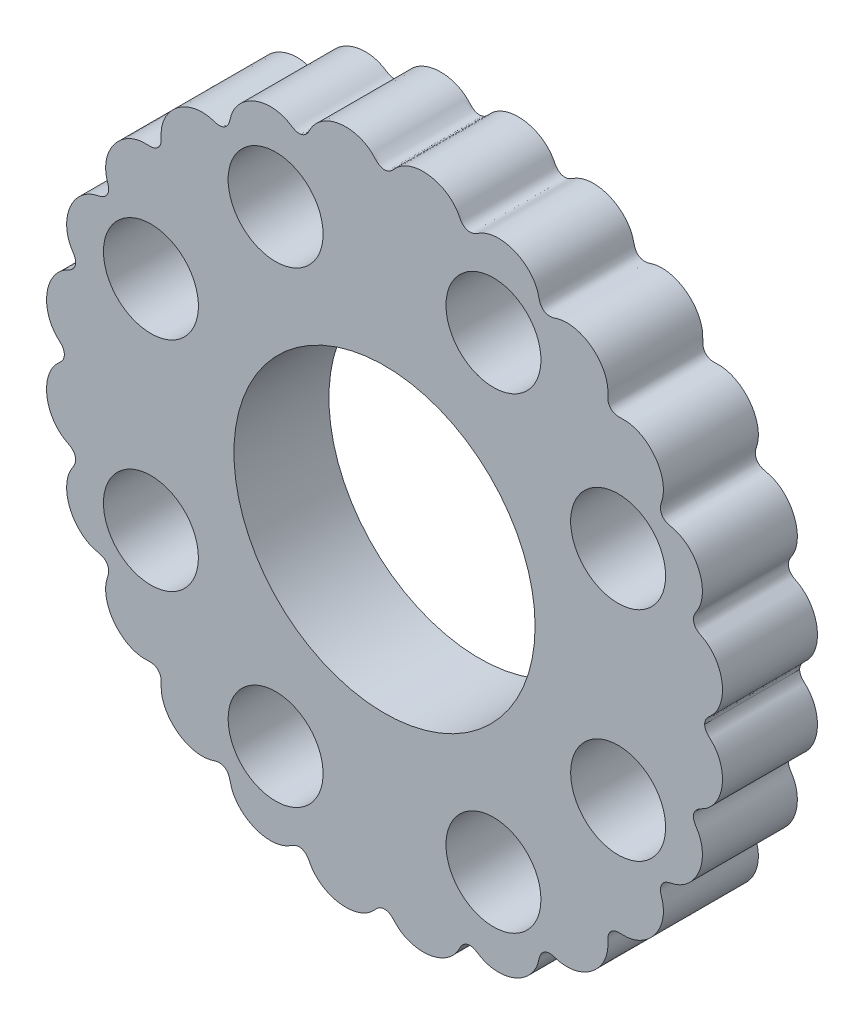
SolidWorks part; units mm, degrees
ref_plane "Plan de face" through (0, 0, 0) normal (0, 0, 1) x (1, 0, 0)
ref_plane "Plan de dessus" through (0, 0, 0) normal (0, 1, 0) x (1, 0, 0)
ref_plane "Plan de droite" through (0, 0, 0) normal (1, 0, 0) x (0, 0, -1)
sketch "Esquisse1" plane through (0, 0, 0) normal (0, 0, 1) x (1, 0, 0)
  line L0 (-1000, 0) -> (49000, 0) construction
  spline S0 degree 4 poles (22.9955, 6.6042) (22.9643, 6.5397) (22.914, 6.4032) (22.9023, 6.1862) (23.0214, 5.9244) (23.2219, 5.7605) (23.4288, 5.659) (23.6594, 5.5306) (23.9059, 5.3649) (24.1666, 5.1353) (24.4254, 4.835) (24.6422, 4.5029) (24.8162, 4.1468) (24.946, 3.7722) (25.0308, 3.385) (25.0698, 2.9906) (25.0624, 2.5943) (25.0079, 2.2017) (24.9068, 1.8224) (24.7781, 1.5066) (24.64, 1.2523) (24.5081, 1.0548) (24.3917, 0.9046) (24.2647, 0.7631) (24.1289, 0.6302) (24.012, 0.5251) (23.9248, 0.4355) (23.8688, 0.3622) (23.8363, 0.3122) (23.8082, 0.2597) (23.7852, 0.2044) (23.7697, 0.1547) (23.76, 0.1121) (23.7533, 0.0661) (23.7501, 0.0228) (23.7495, -0.004) (23.7513, -0.04) (23.7542, -0.0715) (23.7595, -0.1093) (23.7688, -0.1512) (23.7835, -0.1997) (23.8056, -0.2538) (23.8324, -0.3054) (23.8635, -0.3546) (23.9194, -0.4297) (24.009, -0.5227) (24.1313, -0.6322) (24.2737, -0.7721) (24.4392, -0.959) (24.6145, -1.2025) (24.7855, -1.5135) (24.9316, -1.8961) (25.0271, -2.299) (25.0708, -2.7153) (25.0622, -3.1311) (25.0033, -3.5401) (24.8958, -3.9363) (24.7419, -4.314) (24.5445, -4.6645) (24.307, -4.9822) (24.0331, -5.2614) (23.7654, -5.4667) (23.5164, -5.6129) (23.2956, -5.7243) (23.1195, -5.8363) (22.9763, -6.0087) (22.9044, -6.234) (22.925, -6.462) (23.0164, -6.6581) (23.1266, -6.8267) (23.2244, -6.9889) (23.3341, -7.1984) (23.4412, -7.4619) (23.5336, -7.7957) (23.5876, -8.2004) (23.5865, -8.623) (23.5267, -9.0558) (23.3808, -9.5868) (23.1436, -10.0885) (22.8209, -10.5434) (22.4327, -10.9196) (22.1006, -11.1627) (21.7948, -11.3267) (21.5321, -11.4304) (21.3065, -11.4954) (21.1232, -11.5381) (20.9306, -11.5808) (20.7385, -11.6689) (20.5325, -11.8672) (20.4495, -12.16) (20.5219, -12.4298) (20.6167, -12.7241) (20.6818, -13.0067) (20.7176, -13.3406) (20.7046, -13.7295) (20.6405, -14.1156) (20.5273, -14.4945) (20.3673, -14.8595) (20.1602, -15.2112) (19.9061, -15.5428) (19.6059, -15.8469) (19.261, -16.115) (18.8955, -16.3273) (18.5181, -16.4829) (18.1828, -16.5697) (17.9011, -16.6087) (17.6647, -16.6185) (17.4754, -16.6149) (17.2743, -16.6037) (17.0588, -16.6226) (16.851, -16.7187) (16.6918, -16.8937) (16.6141, -17.104) (16.6052, -17.3124) (16.6191, -17.5593) (16.617, -17.8481) (16.5731, -18.1826) (16.4683, -18.5594) (16.3118, -18.9239) (16.107, -19.2701) (15.8569, -19.5923) (15.5674, -19.8834) (15.2427, -20.1389) (14.8869, -20.3543) (14.5046, -20.5246) (14.1078, -20.6433) (13.7035, -20.7081) (13.2985, -20.7166) (12.9508, -20.673) (12.6603, -20.5981) (12.4161, -20.517) (12.2029, -20.4723) (11.9744, -20.5019) (11.768, -20.6211) (11.6281, -20.8042) (11.5602, -21.0112) (11.5084, -21.2632) (11.428, -21.5523) (11.2919, -21.8752) (11.082, -22.2216) (10.8237, -22.5394) (10.5226, -22.8236) (10.1839, -23.0696) (9.8195, -23.2701) (9.4358, -23.4235) (9.039, -23.5286) (8.6349, -23.5841) (8.2327, -23.5884) (7.8388, -23.5416) (7.4601, -23.444) (7.1484, -23.3148) (6.8973, -23.1723) (6.6904, -23.0367) (6.5054, -22.9402) (6.2844, -22.9024) (6.0534, -22.9528) (5.8662, -23.0846) (5.7421, -23.2618) (5.6512, -23.4416) (5.5596, -23.6073) (5.4331, -23.8072) (5.2584, -24.0316) (5.0155, -24.2786) (4.6921, -24.5276) (4.2308, -24.7924) (3.7121, -24.9769) (3.1672, -25.0695) (2.6142, -25.0665) (2.1723, -25.0046) (1.7597, -24.8871) (1.3831, -24.721) (1.0882, -24.5382) (0.867, -24.3625) (0.6979, -24.1997) (0.5693, -24.0623) (0.436, -23.9168) (0.2637, -23.7945) (-0.011, -23.7153) (-0.3061, -23.7898) (-0.5036, -23.9874) (-0.7111, -24.2166) (-0.9232, -24.4143) (-1.1945, -24.6122) (-1.5378, -24.7955) (-1.9042, -24.933) (-2.289, -25.0244) (-2.6851, -25.0684) (-3.0932, -25.0648) (-3.5074, -25.0106) (-3.9209, -24.9026) (-4.3256, -24.738) (-4.6921, -24.5276) (-5.0155, -24.2786) (-5.2584, -24.0316) (-5.4331, -23.8072) (-5.5596, -23.6073) (-5.6512, -23.4416) (-5.7421, -23.2618) (-5.8662, -23.0846) (-6.0534, -22.9528) (-6.2844, -22.9024) (-6.5054, -22.9402) (-6.6904, -23.0367) (-6.8973, -23.1723) (-7.1484, -23.3148) (-7.4601, -23.444) (-7.8388, -23.5416) (-8.2327, -23.5884) (-8.6349, -23.5841) (-9.039, -23.5286) (-9.4358, -23.4235) (-9.8195, -23.2701) (-10.1839, -23.0696) (-10.5226, -22.8236) (-10.8237, -22.5394) (-11.082, -22.2216) (-11.2919, -21.8752) (-11.428, -21.5523) (-11.5084, -21.2632) (-11.5602, -21.0112) (-11.6281, -20.8042) (-11.768, -20.6211) (-11.9744, -20.5019) (-12.2029, -20.4723) (-12.4161, -20.517) (-12.6603, -20.5981) (-12.9508, -20.673) (-13.2985, -20.7166) (-13.7035, -20.7081) (-14.1078, -20.6433) (-14.6048, -20.4946) (-15.1642, -20.2163) (-15.6552, -19.8308) (-16.055, -19.3579) (-16.3118, -18.9239) (-16.4683, -18.5594) (-16.5731, -18.1826) (-16.617, -17.8481) (-16.6191, -17.5593) (-16.6052, -17.3124) (-16.6141, -17.104) (-16.6918, -16.8937) (-16.851, -16.7187) (-17.0588, -16.6226) (-17.2743, -16.6037) (-17.4754, -16.6149) (-17.6647, -16.6185) (-17.9011, -16.6087) (-18.1828, -16.5697) (-18.5181, -16.4829) (-18.8955, -16.3273) (-19.261, -16.1151) (-19.6059, -15.8469) (-19.9061, -15.5428) (-20.1602, -15.2112) (-20.3673, -14.8595) (-20.5273, -14.4945) (-20.6405, -14.1156) (-20.7046, -13.7294) (-20.7175, -13.3407) (-20.6818, -13.0066) (-20.6166, -12.7243) (-20.522, -12.4295) (-20.4494, -12.1605) (-20.5243, -11.8962) (-20.683, -11.7227) (-20.8176, -11.632) (-20.958, -11.5755) (-21.1234, -11.5373) (-21.3064, -11.4958) (-21.5321, -11.4302) (-21.7948, -11.3268) (-22.1006, -11.1626) (-22.4327, -10.9196) (-22.7408, -10.6211) (-23.0153, -10.2693) (-23.2393, -9.8862) (-23.4104, -9.4792) (-23.5267, -9.0558) (-23.5865, -8.623) (-23.5876, -8.2004) (-23.5336, -7.7957) (-23.4412, -7.4619) (-23.3341, -7.1984) (-23.2244, -6.9889) (-23.1266, -6.8267) (-23.0164, -6.6581) (-22.925, -6.462) (-22.9044, -6.234) (-22.9763, -6.0087) (-23.1195, -5.8363) (-23.2956, -5.7243) (-23.5164, -5.6129) (-23.7654, -5.4667) (-24.0331, -5.2614) (-24.307, -4.9822) (-24.5445, -4.6645) (-24.7419, -4.314) (-24.8958, -3.9363) (-25.0033, -3.5401) (-25.0622, -3.1311) (-25.0708, -2.7153) (-25.0271, -2.299) (-24.9316, -1.8961) (-24.7855, -1.5135) (-24.6145, -1.2025) (-24.4393, -0.959) (-24.2737, -0.7721) (-24.1313, -0.6321) (-23.9982, -0.5131) (-23.8995, -0.4084) (-23.8391, -0.3182) (-23.8055, -0.2539) (-23.7835, -0.1997) (-23.7688, -0.1512) (-23.7595, -0.1093) (-23.7542, -0.0715) (-23.7513, -0.04) (-23.7495, -0.0037) (-23.7502, 0.0234) (-23.7534, 0.0677) (-23.7604, 0.1144) (-23.7705, 0.1578) (-23.7867, 0.2087) (-23.8107, 0.2649) (-23.8399, 0.3183) (-23.8736, 0.369) (-23.9317, 0.4432) (-24.0215, 0.5339) (-24.141, 0.6413) (-24.279, 0.7779) (-24.4075, 0.9235) (-24.5249, 1.0783) (-24.6575, 1.2816) (-24.7976, 1.5478) (-24.9275, 1.8824) (-25.0256, 2.2876) (-25.071, 2.7111) (-25.0623, 3.1368) (-25.0002, 3.5582) (-24.8859, 3.9683) (-24.7199, 4.3608) (-24.4999, 4.7349) (-24.2231, 5.0813) (-23.9331, 5.3469) (-23.6469, 5.5411) (-23.3456, 5.7009) (-23.0735, 5.8417) (-22.8982, 6.1368) (-22.9147, 6.4027) (-22.9638, 6.54) (-22.9956, 6.6042) knots 0 0 0 0 0 0.002762 0.005524 0.008057 0.010589 0.012487 0.014385 0.018181 0.021977 0.025773 0.029569 0.033366 0.037162 0.040959 0.044755 0.048552 0.052348 0.056144 0.059791 0.061614 0.063437 0.06526 0.067083 0.068906 0.070729 0.071301 0.071873 0.072445 0.073016 0.073588 0.07416 0.074446 0.074731 0.075303 0.075582 0.075861 0.07614 0.076419 0.076977 0.077535 0.078093 0.078652 0.07921 0.079768 0.081683 0.083599 0.085515 0.08743 0.091261 0.095093 0.099101 0.103109 0.107118 0.111126 0.115032 0.118938 0.122843 0.126749 0.130438 0.134127 0.137815 0.13966 0.141504 0.143638 0.145771 0.148068 0.150364 0.15218 0.153996 0.155812 0.157628 0.16126 0.164892 0.169075 0.173257 0.177439 0.181621 0.190162 0.194433 0.198704 0.20231 0.205917 0.20772 0.209523 0.211327 0.21313 0.215313 0.217496 0.222107 0.223949 0.225791 0.229476 0.23316 0.236844 0.240662 0.24448 0.248298 0.252116 0.256299 0.260481 0.264663 0.268845 0.272477 0.276109 0.277925 0.279741 0.281557 0.283373 0.28567 0.287966 0.2901 0.292233 0.294078 0.295922 0.299611 0.3033 0.306988 0.310894 0.3148 0.318706 0.322612 0.32662 0.330628 0.334637 0.338645 0.342476 0.346307 0.350139 0.352054 0.35397 0.356202 0.358434 0.360667 0.362899 0.364815 0.36673 0.370561 0.374393 0.378224 0.382232 0.386241 0.390249 0.394257 0.398163 0.402069 0.405975 0.40988 0.413569 0.417258 0.420947 0.422791 0.424635 0.426769 0.428902 0.431199 0.433495 0.435311 0.437127 0.438943 0.440759 0.444392 0.448024 0.452206 0.456388 0.464752 0.469023 0.473294 0.477564 0.481835 0.485441 0.489048 0.490851 0.492655 0.494458 0.496261 0.498444 0.500627 0.505239 0.507081 0.508923 0.512607 0.516291 0.519975 0.523793 0.527611 0.53143 0.535248 0.53943 0.543612 0.547794 0.551976 0.555609 0.559241 0.561057 0.562873 0.564689 0.566505 0.568801 0.571098 0.573231 0.575365 0.577209 0.579053 0.582742 0.586431 0.59012 0.594025 0.597931 0.601837 0.605743 0.609751 0.61376 0.617768 0.621776 0.625607 0.629439 0.63327 0.635186 0.637101 0.639333 0.641566 0.643798 0.64603 0.647946 0.649861 0.653693 0.657524 0.661355 0.665364 0.669372 0.677388 0.6852 0.689106 0.693012 0.6967 0.700389 0.704078 0.705922 0.707767 0.7099 0.712034 0.71433 0.716627 0.718443 0.720259 0.722075 0.723891 0.727523 0.731155 0.735337 0.739519 0.743701 0.747884 0.751702 0.75552 0.759338 0.763156 0.76684 0.770525 0.774209 0.776051 0.777893 0.782504 0.784687 0.785779 0.78687 0.788673 0.790477 0.79228 0.794083 0.79769 0.801296 0.805567 0.809838 0.814108 0.818379 0.822561 0.826743 0.830926 0.835108 0.83874 0.842372 0.844188 0.846004 0.84782 0.849636 0.851932 0.854229 0.856362 0.858496 0.86034 0.862185 0.865873 0.869562 0.873251 0.877157 0.881063 0.884968 0.888874 0.892882 0.896891 0.900899 0.904907 0.908739 0.91257 0.914486 0.916401 0.918317 0.920232 0.921349 0.921907 0.922465 0.923023 0.923581 0.92386 0.924139 0.924418 0.924697 0.925281 0.925573 0.925865 0.926449 0.927033 0.927617 0.928201 0.928785 0.929369 0.931232 0.933095 0.934957 0.93682 0.938683 0.940546 0.944272 0.94835 0.952428 0.956506 0.960584 0.964661 0.968739 0.972817 0.976894 0.98129 0.985685 0.987883 0.99008 0.994476 0.997238 1 1 1 1 1 construction
  spline S1 degree 4 poles (23.75, 0) (23.75, -0.0062) (23.7502, -0.0186) (23.7513, -0.04) (23.7542, -0.0715) (23.7595, -0.1093) (23.7688, -0.1512) (23.7835, -0.1997) (23.8056, -0.2538) (23.8324, -0.3054) (23.8635, -0.3546) (23.9194, -0.4297) (24.009, -0.5227) (24.1313, -0.6322) (24.2737, -0.7721) (24.4392, -0.959) (24.6145, -1.2025) (24.7855, -1.5135) (24.9316, -1.8961) (25.0271, -2.299) (25.0708, -2.7153) (25.0622, -3.1311) (25.0033, -3.5401) (24.8958, -3.9363) (24.7419, -4.314) (24.5445, -4.6645) (24.307, -4.9822) (24.0331, -5.2614) (23.7654, -5.4667) (23.5164, -5.6129) (23.2956, -5.7243) (23.1195, -5.8363) (22.9763, -6.0087) (22.9044, -6.234) (22.925, -6.462) (23.0164, -6.6581) (23.1266, -6.8267) (23.2244, -6.9889) (23.3341, -7.1984) (23.4412, -7.4619) (23.5336, -7.7957) (23.5876, -8.2004) (23.5865, -8.623) (23.5267, -9.0558) (23.3808, -9.5868) (23.1436, -10.0885) (22.8209, -10.5434) (22.4327, -10.9196) (22.1006, -11.1627) (21.7948, -11.3267) (21.5321, -11.4304) (21.3065, -11.4954) (21.1232, -11.5381) (20.9306, -11.5808) (20.7385, -11.6689) (20.5325, -11.8672) (20.4495, -12.16) (20.5219, -12.4298) (20.6167, -12.7241) (20.6818, -13.0067) (20.7176, -13.3406) (20.7046, -13.7295) (20.6405, -14.1156) (20.5273, -14.4945) (20.3673, -14.8595) (20.1602, -15.2112) (19.9061, -15.5428) (19.6059, -15.8469) (19.261, -16.115) (18.8955, -16.3273) (18.5181, -16.4829) (18.1828, -16.5697) (17.9011, -16.6087) (17.6647, -16.6185) (17.4754, -16.6149) (17.2743, -16.6037) (17.0588, -16.6226) (16.851, -16.7187) (16.6918, -16.8937) (16.6141, -17.104) (16.6052, -17.3124) (16.6191, -17.5593) (16.617, -17.8481) (16.5731, -18.1826) (16.4683, -18.5594) (16.3118, -18.9239) (16.107, -19.2701) (15.8569, -19.5923) (15.5674, -19.8834) (15.2427, -20.1389) (14.8869, -20.3543) (14.5046, -20.5246) (14.1078, -20.6433) (13.7035, -20.7081) (13.2985, -20.7166) (12.9508, -20.673) (12.6603, -20.5981) (12.4161, -20.517) (12.2029, -20.4723) (11.9744, -20.5019) (11.768, -20.6211) (11.6281, -20.8042) (11.5602, -21.0112) (11.5084, -21.2632) (11.428, -21.5523) (11.2919, -21.8752) (11.082, -22.2216) (10.8237, -22.5394) (10.5226, -22.8236) (10.1839, -23.0696) (9.8195, -23.2701) (9.4358, -23.4235) (9.039, -23.5286) (8.6349, -23.5841) (8.2327, -23.5884) (7.8388, -23.5416) (7.4601, -23.444) (7.1484, -23.3148) (6.8973, -23.1723) (6.6904, -23.0367) (6.5054, -22.9402) (6.2844, -22.9024) (6.0534, -22.9528) (5.8662, -23.0846) (5.7421, -23.2618) (5.6512, -23.4416) (5.5596, -23.6073) (5.4331, -23.8072) (5.2584, -24.0316) (5.0155, -24.2786) (4.6921, -24.5276) (4.2308, -24.7924) (3.7121, -24.9769) (3.1672, -25.0695) (2.6142, -25.0665) (2.1723, -25.0046) (1.7597, -24.8871) (1.3831, -24.721) (1.0882, -24.5382) (0.867, -24.3625) (0.6979, -24.1997) (0.5693, -24.0623) (0.436, -23.9168) (0.2637, -23.7945) (-0.011, -23.7153) (-0.3061, -23.7898) (-0.5036, -23.9874) (-0.7111, -24.2166) (-0.9232, -24.4143) (-1.1945, -24.6122) (-1.5378, -24.7955) (-1.9042, -24.933) (-2.289, -25.0244) (-2.6851, -25.0684) (-3.0932, -25.0648) (-3.5074, -25.0106) (-3.9209, -24.9026) (-4.3256, -24.738) (-4.6921, -24.5276) (-5.0155, -24.2786) (-5.2584, -24.0316) (-5.4331, -23.8072) (-5.5596, -23.6073) (-5.6512, -23.4416) (-5.7421, -23.2618) (-5.8662, -23.0846) (-6.0534, -22.9528) (-6.2844, -22.9024) (-6.5054, -22.9402) (-6.6904, -23.0367) (-6.8973, -23.1723) (-7.1484, -23.3148) (-7.4601, -23.444) (-7.8388, -23.5416) (-8.2327, -23.5884) (-8.6349, -23.5841) (-9.039, -23.5286) (-9.4358, -23.4235) (-9.8195, -23.2701) (-10.1839, -23.0696) (-10.5226, -22.8236) (-10.8237, -22.5394) (-11.082, -22.2216) (-11.2919, -21.8752) (-11.428, -21.5523) (-11.5084, -21.2632) (-11.5602, -21.0112) (-11.6281, -20.8042) (-11.768, -20.6211) (-11.9744, -20.5019) (-12.2029, -20.4723) (-12.4161, -20.517) (-12.6603, -20.5981) (-12.9508, -20.673) (-13.2985, -20.7166) (-13.7035, -20.7081) (-14.1078, -20.6433) (-14.6048, -20.4946) (-15.1642, -20.2163) (-15.6552, -19.8308) (-16.055, -19.3579) (-16.3118, -18.9239) (-16.4683, -18.5594) (-16.5731, -18.1826) (-16.617, -17.8481) (-16.6191, -17.5593) (-16.6052, -17.3124) (-16.6141, -17.104) (-16.6918, -16.8937) (-16.851, -16.7187) (-17.0588, -16.6226) (-17.2743, -16.6037) (-17.4754, -16.6149) (-17.6647, -16.6185) (-17.9011, -16.6087) (-18.1828, -16.5697) (-18.5181, -16.4829) (-18.8955, -16.3273) (-19.261, -16.1151) (-19.6059, -15.8469) (-19.9061, -15.5428) (-20.1602, -15.2112) (-20.3673, -14.8595) (-20.5273, -14.4945) (-20.6405, -14.1156) (-20.7046, -13.7294) (-20.7175, -13.3407) (-20.6818, -13.0066) (-20.6166, -12.7243) (-20.522, -12.4295) (-20.4494, -12.1605) (-20.5243, -11.8962) (-20.683, -11.7227) (-20.8176, -11.632) (-20.958, -11.5755) (-21.1234, -11.5373) (-21.3064, -11.4958) (-21.5321, -11.4302) (-21.7948, -11.3268) (-22.1006, -11.1626) (-22.4327, -10.9196) (-22.7408, -10.6211) (-23.0153, -10.2693) (-23.2393, -9.8862) (-23.4104, -9.4792) (-23.5267, -9.0558) (-23.5865, -8.623) (-23.5876, -8.2004) (-23.5336, -7.7957) (-23.4412, -7.4619) (-23.3341, -7.1984) (-23.2244, -6.9889) (-23.1266, -6.8267) (-23.0164, -6.6581) (-22.925, -6.462) (-22.9044, -6.234) (-22.9763, -6.0087) (-23.1195, -5.8363) (-23.2956, -5.7243) (-23.5164, -5.6129) (-23.7654, -5.4667) (-24.0331, -5.2614) (-24.307, -4.9822) (-24.5445, -4.6645) (-24.7419, -4.314) (-24.8958, -3.9363) (-25.0033, -3.5401) (-25.0622, -3.1311) (-25.0708, -2.7153) (-25.0271, -2.299) (-24.9316, -1.8961) (-24.7855, -1.5135) (-24.6145, -1.2025) (-24.4393, -0.959) (-24.2737, -0.7721) (-24.1313, -0.6321) (-23.9982, -0.5131) (-23.8995, -0.4084) (-23.8391, -0.3182) (-23.8055, -0.2539) (-23.7835, -0.1997) (-23.7688, -0.1512) (-23.7595, -0.1093) (-23.7542, -0.0715) (-23.7513, -0.04) (-23.7502, -0.0186) (-23.75, -0.0062) (-23.75, 0) knots 0.075303 0.075303 0.075303 0.075303 0.075303 0.075582 0.075861 0.07614 0.076419 0.076977 0.077535 0.078093 0.078652 0.07921 0.079768 0.081683 0.083599 0.085515 0.08743 0.091261 0.095093 0.099101 0.103109 0.107118 0.111126 0.115032 0.118938 0.122843 0.126749 0.130438 0.134127 0.137815 0.13966 0.141504 0.143638 0.145771 0.148068 0.150364 0.15218 0.153996 0.155812 0.157628 0.16126 0.164892 0.169075 0.173257 0.177439 0.181621 0.190162 0.194433 0.198704 0.20231 0.205917 0.20772 0.209523 0.211327 0.21313 0.215313 0.217496 0.222107 0.223949 0.225791 0.229476 0.23316 0.236844 0.240662 0.24448 0.248298 0.252116 0.256299 0.260481 0.264663 0.268845 0.272477 0.276109 0.277925 0.279741 0.281557 0.283373 0.28567 0.287966 0.2901 0.292233 0.294078 0.295922 0.299611 0.3033 0.306988 0.310894 0.3148 0.318706 0.322612 0.32662 0.330628 0.334637 0.338645 0.342476 0.346307 0.350139 0.352054 0.35397 0.356202 0.358434 0.360667 0.362899 0.364815 0.36673 0.370561 0.374393 0.378224 0.382232 0.386241 0.390249 0.394257 0.398163 0.402069 0.405975 0.40988 0.413569 0.417258 0.420947 0.422791 0.424635 0.426769 0.428902 0.431199 0.433495 0.435311 0.437127 0.438943 0.440759 0.444392 0.448024 0.452206 0.456388 0.464752 0.469023 0.473294 0.477564 0.481835 0.485441 0.489048 0.490851 0.492655 0.494458 0.496261 0.498444 0.500627 0.505239 0.507081 0.508923 0.512607 0.516291 0.519975 0.523793 0.527611 0.53143 0.535248 0.53943 0.543612 0.547794 0.551976 0.555609 0.559241 0.561057 0.562873 0.564689 0.566505 0.568801 0.571098 0.573231 0.575365 0.577209 0.579053 0.582742 0.586431 0.59012 0.594025 0.597931 0.601837 0.605743 0.609751 0.61376 0.617768 0.621776 0.625607 0.629439 0.63327 0.635186 0.637101 0.639333 0.641566 0.643798 0.64603 0.647946 0.649861 0.653693 0.657524 0.661355 0.665364 0.669372 0.677388 0.6852 0.689106 0.693012 0.6967 0.700389 0.704078 0.705922 0.707767 0.7099 0.712034 0.71433 0.716627 0.718443 0.720259 0.722075 0.723891 0.727523 0.731155 0.735337 0.739519 0.743701 0.747884 0.751702 0.75552 0.759338 0.763156 0.76684 0.770525 0.774209 0.776051 0.777893 0.782504 0.784687 0.785779 0.78687 0.788673 0.790477 0.79228 0.794083 0.79769 0.801296 0.805567 0.809838 0.814108 0.818379 0.822561 0.826743 0.830926 0.835108 0.83874 0.842372 0.844188 0.846004 0.84782 0.849636 0.851932 0.854229 0.856362 0.858496 0.86034 0.862185 0.865873 0.869562 0.873251 0.877157 0.881063 0.884968 0.888874 0.892882 0.896891 0.900899 0.904907 0.908739 0.91257 0.914486 0.916401 0.918317 0.920232 0.921349 0.921907 0.922465 0.923023 0.923581 0.92386 0.924139 0.924418 0.924697 0.924697 0.924697 0.924697 0.924697 construction
  spline S2 degree 4 poles (23.75, 0) (23.75, 0.0062) (23.7502, 0.0186) (23.7513, 0.04) (23.7542, 0.0715) (23.7595, 0.1093) (23.7688, 0.1512) (23.7835, 0.1997) (23.8056, 0.2538) (23.8324, 0.3054) (23.8635, 0.3546) (23.9194, 0.4297) (24.009, 0.5227) (24.1313, 0.6322) (24.2737, 0.7721) (24.4392, 0.959) (24.6145, 1.2025) (24.7855, 1.5135) (24.9316, 1.8961) (25.0271, 2.299) (25.0708, 2.7153) (25.0622, 3.1311) (25.0033, 3.5401) (24.8958, 3.9363) (24.7419, 4.314) (24.5445, 4.6645) (24.307, 4.9822) (24.0331, 5.2614) (23.7654, 5.4667) (23.5164, 5.6129) (23.2956, 5.7243) (23.1195, 5.8363) (22.9763, 6.0087) (22.9044, 6.234) (22.925, 6.462) (23.0164, 6.6581) (23.1266, 6.8267) (23.2244, 6.9889) (23.3341, 7.1984) (23.4412, 7.4619) (23.5336, 7.7957) (23.5876, 8.2004) (23.5865, 8.623) (23.5267, 9.0558) (23.3808, 9.5868) (23.1436, 10.0885) (22.8209, 10.5434) (22.4327, 10.9196) (22.1006, 11.1627) (21.7948, 11.3267) (21.5321, 11.4304) (21.3065, 11.4954) (21.1232, 11.5381) (20.9306, 11.5808) (20.7385, 11.6689) (20.5325, 11.8672) (20.4495, 12.16) (20.5219, 12.4298) (20.6167, 12.7241) (20.6818, 13.0067) (20.7176, 13.3406) (20.7046, 13.7295) (20.6405, 14.1156) (20.5273, 14.4945) (20.3673, 14.8595) (20.1602, 15.2112) (19.9061, 15.5428) (19.6059, 15.8469) (19.261, 16.115) (18.8955, 16.3273) (18.5181, 16.4829) (18.1828, 16.5697) (17.9011, 16.6087) (17.6647, 16.6185) (17.4754, 16.6149) (17.2743, 16.6037) (17.0588, 16.6226) (16.851, 16.7187) (16.6918, 16.8937) (16.6141, 17.104) (16.6052, 17.3124) (16.6191, 17.5593) (16.617, 17.8481) (16.5731, 18.1826) (16.4683, 18.5594) (16.3118, 18.9239) (16.107, 19.2701) (15.8569, 19.5923) (15.5674, 19.8834) (15.2427, 20.1389) (14.8869, 20.3543) (14.5046, 20.5246) (14.1078, 20.6433) (13.7035, 20.7081) (13.2985, 20.7166) (12.9508, 20.673) (12.6603, 20.5981) (12.4161, 20.517) (12.2029, 20.4723) (11.9744, 20.5019) (11.768, 20.6211) (11.6281, 20.8042) (11.5602, 21.0112) (11.5084, 21.2632) (11.428, 21.5523) (11.2919, 21.8752) (11.082, 22.2216) (10.8237, 22.5394) (10.5226, 22.8236) (10.1839, 23.0696) (9.8195, 23.2701) (9.4358, 23.4235) (9.039, 23.5286) (8.6349, 23.5841) (8.2327, 23.5884) (7.8388, 23.5416) (7.4601, 23.444) (7.1484, 23.3148) (6.8973, 23.1723) (6.6904, 23.0367) (6.5054, 22.9402) (6.2844, 22.9024) (6.0534, 22.9528) (5.8662, 23.0846) (5.7421, 23.2618) (5.6512, 23.4416) (5.5596, 23.6073) (5.4331, 23.8072) (5.2584, 24.0316) (5.0155, 24.2786) (4.6921, 24.5276) (4.2308, 24.7924) (3.7121, 24.9769) (3.1672, 25.0695) (2.6142, 25.0665) (2.1723, 25.0046) (1.7597, 24.8871) (1.3831, 24.721) (1.0882, 24.5382) (0.867, 24.3625) (0.6979, 24.1997) (0.5693, 24.0623) (0.436, 23.9168) (0.2637, 23.7945) (-0.011, 23.7153) (-0.3061, 23.7898) (-0.5036, 23.9874) (-0.7111, 24.2166) (-0.9232, 24.4143) (-1.1945, 24.6122) (-1.5378, 24.7955) (-1.9042, 24.933) (-2.289, 25.0244) (-2.6851, 25.0684) (-3.0932, 25.0648) (-3.5074, 25.0106) (-3.9209, 24.9026) (-4.3256, 24.738) (-4.6921, 24.5276) (-5.0155, 24.2786) (-5.2584, 24.0316) (-5.4331, 23.8072) (-5.5596, 23.6073) (-5.6512, 23.4416) (-5.7421, 23.2618) (-5.8662, 23.0846) (-6.0534, 22.9528) (-6.2844, 22.9024) (-6.5054, 22.9402) (-6.6904, 23.0367) (-6.8973, 23.1723) (-7.1484, 23.3148) (-7.4601, 23.444) (-7.8388, 23.5416) (-8.2327, 23.5884) (-8.6349, 23.5841) (-9.039, 23.5286) (-9.4358, 23.4235) (-9.8195, 23.2701) (-10.1839, 23.0696) (-10.5226, 22.8236) (-10.8237, 22.5394) (-11.082, 22.2216) (-11.2919, 21.8752) (-11.428, 21.5523) (-11.5084, 21.2632) (-11.5602, 21.0112) (-11.6281, 20.8042) (-11.768, 20.6211) (-11.9744, 20.5019) (-12.2029, 20.4723) (-12.4161, 20.517) (-12.6603, 20.5981) (-12.9508, 20.673) (-13.2985, 20.7166) (-13.7035, 20.7081) (-14.1078, 20.6433) (-14.6048, 20.4946) (-15.1642, 20.2163) (-15.6552, 19.8308) (-16.055, 19.3579) (-16.3118, 18.9239) (-16.4683, 18.5594) (-16.5731, 18.1826) (-16.617, 17.8481) (-16.6191, 17.5593) (-16.6052, 17.3124) (-16.6141, 17.104) (-16.6918, 16.8937) (-16.851, 16.7187) (-17.0588, 16.6226) (-17.2743, 16.6037) (-17.4754, 16.6149) (-17.6647, 16.6185) (-17.9011, 16.6087) (-18.1828, 16.5697) (-18.5181, 16.4829) (-18.8955, 16.3273) (-19.261, 16.1151) (-19.6059, 15.8469) (-19.9061, 15.5428) (-20.1602, 15.2112) (-20.3673, 14.8595) (-20.5273, 14.4945) (-20.6405, 14.1156) (-20.7046, 13.7294) (-20.7175, 13.3407) (-20.6818, 13.0066) (-20.6166, 12.7243) (-20.522, 12.4295) (-20.4494, 12.1605) (-20.5243, 11.8962) (-20.683, 11.7227) (-20.8176, 11.632) (-20.958, 11.5755) (-21.1234, 11.5373) (-21.3064, 11.4958) (-21.5321, 11.4302) (-21.7948, 11.3268) (-22.1006, 11.1626) (-22.4327, 10.9196) (-22.7408, 10.6211) (-23.0153, 10.2693) (-23.2393, 9.8862) (-23.4104, 9.4792) (-23.5267, 9.0558) (-23.5865, 8.623) (-23.5876, 8.2004) (-23.5336, 7.7957) (-23.4412, 7.4619) (-23.3341, 7.1984) (-23.2244, 6.9889) (-23.1266, 6.8267) (-23.0164, 6.6581) (-22.925, 6.462) (-22.9044, 6.234) (-22.9763, 6.0087) (-23.1195, 5.8363) (-23.2956, 5.7243) (-23.5164, 5.6129) (-23.7654, 5.4667) (-24.0331, 5.2614) (-24.307, 4.9822) (-24.5445, 4.6645) (-24.7419, 4.314) (-24.8958, 3.9363) (-25.0033, 3.5401) (-25.0622, 3.1311) (-25.0708, 2.7153) (-25.0271, 2.299) (-24.9316, 1.8961) (-24.7855, 1.5135) (-24.6145, 1.2025) (-24.4393, 0.959) (-24.2737, 0.7721) (-24.1313, 0.6321) (-23.9982, 0.5131) (-23.8995, 0.4084) (-23.8391, 0.3182) (-23.8055, 0.2539) (-23.7835, 0.1997) (-23.7688, 0.1512) (-23.7595, 0.1093) (-23.7542, 0.0715) (-23.7513, 0.04) (-23.7502, 0.0186) (-23.75, 0.0062) (-23.75, 0) knots 0.075303 0.075303 0.075303 0.075303 0.075303 0.075582 0.075861 0.07614 0.076419 0.076977 0.077535 0.078093 0.078652 0.07921 0.079768 0.081683 0.083599 0.085515 0.08743 0.091261 0.095093 0.099101 0.103109 0.107118 0.111126 0.115032 0.118938 0.122843 0.126749 0.130438 0.134127 0.137815 0.13966 0.141504 0.143638 0.145771 0.148068 0.150364 0.15218 0.153996 0.155812 0.157628 0.16126 0.164892 0.169075 0.173257 0.177439 0.181621 0.190162 0.194433 0.198704 0.20231 0.205917 0.20772 0.209523 0.211327 0.21313 0.215313 0.217496 0.222107 0.223949 0.225791 0.229476 0.23316 0.236844 0.240662 0.24448 0.248298 0.252116 0.256299 0.260481 0.264663 0.268845 0.272477 0.276109 0.277925 0.279741 0.281557 0.283373 0.28567 0.287966 0.2901 0.292233 0.294078 0.295922 0.299611 0.3033 0.306988 0.310894 0.3148 0.318706 0.322612 0.32662 0.330628 0.334637 0.338645 0.342476 0.346307 0.350139 0.352054 0.35397 0.356202 0.358434 0.360667 0.362899 0.364815 0.36673 0.370561 0.374393 0.378224 0.382232 0.386241 0.390249 0.394257 0.398163 0.402069 0.405975 0.40988 0.413569 0.417258 0.420947 0.422791 0.424635 0.426769 0.428902 0.431199 0.433495 0.435311 0.437127 0.438943 0.440759 0.444392 0.448024 0.452206 0.456388 0.464752 0.469023 0.473294 0.477564 0.481835 0.485441 0.489048 0.490851 0.492655 0.494458 0.496261 0.498444 0.500627 0.505239 0.507081 0.508923 0.512607 0.516291 0.519975 0.523793 0.527611 0.53143 0.535248 0.53943 0.543612 0.547794 0.551976 0.555609 0.559241 0.561057 0.562873 0.564689 0.566505 0.568801 0.571098 0.573231 0.575365 0.577209 0.579053 0.582742 0.586431 0.59012 0.594025 0.597931 0.601837 0.605743 0.609751 0.61376 0.617768 0.621776 0.625607 0.629439 0.63327 0.635186 0.637101 0.639333 0.641566 0.643798 0.64603 0.647946 0.649861 0.653693 0.657524 0.661355 0.665364 0.669372 0.677388 0.6852 0.689106 0.693012 0.6967 0.700389 0.704078 0.705922 0.707767 0.7099 0.712034 0.71433 0.716627 0.718443 0.720259 0.722075 0.723891 0.727523 0.731155 0.735337 0.739519 0.743701 0.747884 0.751702 0.75552 0.759338 0.763156 0.76684 0.770525 0.774209 0.776051 0.777893 0.782504 0.784687 0.785779 0.78687 0.788673 0.790477 0.79228 0.794083 0.79769 0.801296 0.805567 0.809838 0.814108 0.818379 0.822561 0.826743 0.830926 0.835108 0.83874 0.842372 0.844188 0.846004 0.84782 0.849636 0.851932 0.854229 0.856362 0.858496 0.86034 0.862185 0.865873 0.869562 0.873251 0.877157 0.881063 0.884968 0.888874 0.892882 0.896891 0.900899 0.904907 0.908739 0.91257 0.914486 0.916401 0.918317 0.920232 0.921349 0.921907 0.922465 0.923023 0.923581 0.92386 0.924139 0.924418 0.924697 0.924697 0.924697 0.924697 0.924697 construction
  spline S3 degree 1 poles (23.6, 0) (-23.6, 0) knots 0 0 1 1 construction
  spline S4 degree 1 poles (23.6, 0) (-23.6, 0) knots 0 0 1 1 construction
  spline S5 degree 3 poles (23.6, 0) (23.6, 0.1413) (23.695, 0.4365) (23.9841, 0.7) (24.2141, 0.9221) (24.4859, 1.2659) (24.7382, 1.7532) (24.9028, 2.3953) (24.9291, 3.0585) (24.8201, 3.7136) (24.5796, 4.3319) (24.2145, 4.8837) (23.8098, 5.2567) (23.4446, 5.4862) (23.1218, 5.6322) (22.8058, 5.9504) (22.7343, 6.405) (22.9149, 6.792) (23.1004, 7.0616) (23.2413, 7.3578) (23.3797, 7.7712) (23.4552, 8.3172) (23.4005, 8.9778) (23.2102, 9.614) (22.8949, 10.1984) (22.4664, 10.7042) (22.027, 11.0368) (21.6368, 11.2314) (21.3278, 11.341) (21.0066, 11.4006) (20.6047, 11.5464) (20.3336, 11.9192) (20.3321, 12.366) (20.4572, 12.6992) (20.5531, 13.1186) (20.5755, 13.6691) (20.4435, 14.3172) (20.1764, 14.9246) (19.7902, 15.4648) (19.3027, 15.9152) (18.7322, 16.2529) (18.2093, 16.419) (17.7739, 16.4699) (17.4549, 16.4641) (17.0624, 16.4473) (16.6542, 16.6542) (16.4474, 17.0623) (16.464, 17.4549) (16.47, 17.7738) (16.419, 18.2094) (16.2529, 18.7322) (15.9152, 19.3027) (15.4649, 19.7902) (14.9246, 20.1764) (14.3173, 20.4435) (13.669, 20.5755) (13.119, 20.5531) (12.6986, 20.4572) (12.367, 20.3322) (11.9185, 20.3338) (11.5466, 20.6046) (11.4006, 21.0058) (11.3413, 21.3277) (11.2312, 21.6369) (11.0369, 22.0269) (10.7042, 22.4665) (10.1983, 22.8949) (9.614, 23.2102) (8.9778, 23.4005) (8.3172, 23.4552) (7.7711, 23.3797) (7.3579, 23.2413) (7.0615, 23.1004) (6.7919, 22.9149) (6.4049, 22.7343) (5.9505, 22.8058) (5.6322, 23.1217) (5.4863, 23.4443) (5.2567, 23.81) (4.8837, 24.2144) (4.3318, 24.5796) (3.7136, 24.8201) (3.0585, 24.9291) (2.3953, 24.9028) (1.7531, 24.7382) (1.2659, 24.4859) (0.9221, 24.2142) (0.7002, 23.9842) (0.4345, 23.6948) (0.0001, 23.5526) (-0.4343, 23.6948) (-0.7014, 23.9846) (-0.9213, 24.2137) (-1.2665, 24.4862) (-1.753, 24.7381) (-2.3954, 24.9028) (-3.0585, 24.9291) (-3.7136, 24.8201) (-4.3319, 24.5796) (-4.8837, 24.2144) (-5.2567, 23.81) (-5.4863, 23.4443) (-5.6322, 23.1217) (-5.9505, 22.8058) (-6.4049, 22.7343) (-6.7919, 22.9149) (-7.0615, 23.1004) (-7.3579, 23.2413) (-7.7711, 23.3797) (-8.3172, 23.4552) (-8.9778, 23.4005) (-9.614, 23.2102) (-10.1983, 22.8949) (-10.7042, 22.4665) (-11.0369, 22.0269) (-11.2312, 21.6369) (-11.3413, 21.3277) (-11.4006, 21.0058) (-11.5466, 20.6046) (-11.9185, 20.3338) (-12.367, 20.3322) (-12.6986, 20.4572) (-13.119, 20.5531) (-13.669, 20.5755) (-14.3173, 20.4435) (-14.9246, 20.1764) (-15.4649, 19.7902) (-15.9152, 19.3027) (-16.2529, 18.7322) (-16.419, 18.2094) (-16.47, 17.7738) (-16.464, 17.4549) (-16.4474, 17.0623) (-16.6542, 16.6542) (-17.0624, 16.4473) (-17.4549, 16.4641) (-17.7739, 16.4699) (-18.2093, 16.419) (-18.7322, 16.2529) (-19.3027, 15.9152) (-19.7902, 15.4648) (-20.1764, 14.9246) (-20.4435, 14.3172) (-20.5755, 13.6691) (-20.5531, 13.1187) (-20.4572, 12.6991) (-20.3321, 12.3662) (-20.3337, 11.919) (-20.6044, 11.5468) (-21.0061, 11.4007) (-21.3278, 11.3412) (-21.6369, 11.2312) (-22.0269, 11.0369) (-22.4664, 10.7042) (-22.8949, 10.1984) (-23.2102, 9.614) (-23.4005, 8.9778) (-23.4552, 8.3172) (-23.3797, 7.7712) (-23.2413, 7.3578) (-23.1004, 7.0616) (-22.9149, 6.792) (-22.7343, 6.405) (-22.8058, 5.9504) (-23.1218, 5.6322) (-23.4446, 5.4862) (-23.8098, 5.2567) (-24.2145, 4.8837) (-24.5796, 4.3319) (-24.8201, 3.7136) (-24.9291, 3.0585) (-24.9028, 2.3953) (-24.7382, 1.7531) (-24.4859, 1.2659) (-24.2141, 0.9221) (-23.9842, 0.7001) (-23.6948, 0.4363) (-23.6, 0.1412) (-23.6, 0) knots 0.075303 0.075303 0.075303 0.075303 0.078621 0.081939 0.085257 0.088575 0.095211 0.101847 0.108483 0.115118 0.121754 0.12839 0.135026 0.138344 0.141662 0.14498 0.148298 0.151616 0.154934 0.158252 0.16157 0.168206 0.174841 0.181477 0.188113 0.194749 0.201385 0.204703 0.208021 0.211339 0.214657 0.217975 0.221293 0.224611 0.227929 0.234564 0.2412 0.247836 0.254472 0.261108 0.267744 0.27438 0.277698 0.281016 0.284334 0.287652 0.29097 0.294287 0.297605 0.300923 0.307559 0.314195 0.320831 0.327467 0.334103 0.340739 0.347375 0.350693 0.35401 0.357328 0.360646 0.363964 0.367282 0.3706 0.373918 0.380554 0.38719 0.393826 0.400462 0.407098 0.413733 0.417051 0.420369 0.423687 0.427005 0.430323 0.433641 0.436959 0.440277 0.446913 0.453549 0.460185 0.466821 0.473456 0.480092 0.486728 0.490046 0.493364 0.496682 0.5 0.503318 0.506636 0.509954 0.513272 0.519908 0.526544 0.533179 0.539815 0.546451 0.553087 0.559723 0.563041 0.566359 0.569677 0.572995 0.576313 0.579631 0.582949 0.586267 0.592902 0.599538 0.606174 0.61281 0.619446 0.626082 0.6294 0.632718 0.636036 0.639354 0.642672 0.64599 0.649308 0.652625 0.659261 0.665897 0.672533 0.679169 0.685805 0.692441 0.699077 0.702395 0.705713 0.709031 0.712348 0.715666 0.718984 0.722302 0.72562 0.732256 0.738892 0.745528 0.752164 0.7588 0.765436 0.772071 0.775389 0.778707 0.782025 0.785343 0.788661 0.791979 0.795297 0.798615 0.805251 0.811887 0.818523 0.825159 0.831794 0.83843 0.841748 0.845066 0.848384 0.851702 0.85502 0.858338 0.861656 0.864974 0.87161 0.878246 0.884882 0.891518 0.898153 0.904789 0.911425 0.914743 0.918061 0.921379 0.924697 0.924697 0.924697 0.924697
  spline S6 degree 3 poles (-23.6, 0) (-23.6, -0.1412) (-23.6948, -0.4363) (-23.9842, -0.7001) (-24.2141, -0.9221) (-24.4859, -1.2659) (-24.7382, -1.7531) (-24.9028, -2.3953) (-24.9291, -3.0585) (-24.8201, -3.7136) (-24.5796, -4.3319) (-24.2145, -4.8837) (-23.8098, -5.2567) (-23.4446, -5.4862) (-23.1218, -5.6322) (-22.8058, -5.9504) (-22.7343, -6.405) (-22.9149, -6.792) (-23.1004, -7.0616) (-23.2413, -7.3578) (-23.3797, -7.7712) (-23.4552, -8.3172) (-23.4005, -8.9778) (-23.2102, -9.614) (-22.8949, -10.1984) (-22.4664, -10.7042) (-22.0269, -11.0369) (-21.6369, -11.2312) (-21.3278, -11.3412) (-21.0061, -11.4007) (-20.6044, -11.5468) (-20.3337, -11.919) (-20.3321, -12.3662) (-20.4572, -12.6991) (-20.5531, -13.1187) (-20.5755, -13.6691) (-20.4435, -14.3172) (-20.1764, -14.9246) (-19.7902, -15.4648) (-19.3027, -15.9152) (-18.7322, -16.2529) (-18.2093, -16.419) (-17.7739, -16.4699) (-17.4549, -16.4641) (-17.0624, -16.4473) (-16.6542, -16.6542) (-16.4474, -17.0623) (-16.464, -17.4549) (-16.47, -17.7738) (-16.419, -18.2094) (-16.2529, -18.7322) (-15.9152, -19.3027) (-15.4649, -19.7902) (-14.9246, -20.1764) (-14.3173, -20.4435) (-13.669, -20.5755) (-13.119, -20.5531) (-12.6986, -20.4572) (-12.367, -20.3322) (-11.9185, -20.3338) (-11.5466, -20.6046) (-11.4006, -21.0058) (-11.3413, -21.3277) (-11.2312, -21.6369) (-11.0369, -22.0269) (-10.7042, -22.4665) (-10.1983, -22.8949) (-9.614, -23.2102) (-8.9778, -23.4005) (-8.3172, -23.4552) (-7.7711, -23.3797) (-7.3579, -23.2413) (-7.0615, -23.1004) (-6.7919, -22.9149) (-6.4049, -22.7343) (-5.9505, -22.8058) (-5.6322, -23.1217) (-5.4863, -23.4443) (-5.2567, -23.81) (-4.8837, -24.2144) (-4.3319, -24.5796) (-3.7136, -24.8201) (-3.0585, -24.9291) (-2.3954, -24.9028) (-1.753, -24.7381) (-1.2665, -24.4862) (-0.9213, -24.2137) (-0.7014, -23.9846) (-0.4343, -23.6948) (0.0001, -23.5526) (0.4345, -23.6948) (0.7002, -23.9842) (0.9221, -24.2142) (1.2659, -24.4859) (1.7531, -24.7382) (2.3953, -24.9028) (3.0585, -24.9291) (3.7136, -24.8201) (4.3318, -24.5796) (4.8837, -24.2144) (5.2567, -23.81) (5.4863, -23.4443) (5.6322, -23.1217) (5.9505, -22.8058) (6.4049, -22.7343) (6.7919, -22.9149) (7.0615, -23.1004) (7.3579, -23.2413) (7.7711, -23.3797) (8.3172, -23.4552) (8.9778, -23.4005) (9.614, -23.2102) (10.1983, -22.8949) (10.7042, -22.4665) (11.0369, -22.0269) (11.2312, -21.6369) (11.3413, -21.3277) (11.4006, -21.0058) (11.5466, -20.6046) (11.9185, -20.3338) (12.367, -20.3322) (12.6986, -20.4572) (13.119, -20.5531) (13.669, -20.5755) (14.3173, -20.4435) (14.9246, -20.1764) (15.4649, -19.7902) (15.9152, -19.3027) (16.2529, -18.7322) (16.419, -18.2094) (16.47, -17.7738) (16.464, -17.4549) (16.4474, -17.0623) (16.6542, -16.6542) (17.0624, -16.4473) (17.4549, -16.4641) (17.7739, -16.4699) (18.2093, -16.419) (18.7322, -16.2529) (19.3027, -15.9152) (19.7902, -15.4648) (20.1764, -14.9246) (20.4435, -14.3172) (20.5755, -13.6691) (20.5531, -13.1186) (20.4572, -12.6992) (20.3321, -12.366) (20.3336, -11.9192) (20.6047, -11.5464) (21.0066, -11.4006) (21.3278, -11.341) (21.6368, -11.2314) (22.027, -11.0368) (22.4664, -10.7042) (22.8949, -10.1984) (23.2102, -9.614) (23.4005, -8.9778) (23.4552, -8.3172) (23.3797, -7.7712) (23.2413, -7.3578) (23.1004, -7.0616) (22.9149, -6.792) (22.7343, -6.405) (22.8058, -5.9504) (23.1218, -5.6322) (23.4446, -5.4862) (23.8098, -5.2567) (24.2145, -4.8837) (24.5796, -4.3319) (24.8201, -3.7136) (24.9291, -3.0585) (24.9028, -2.3953) (24.7382, -1.7532) (24.4859, -1.2659) (24.2141, -0.9221) (23.9841, -0.7) (23.695, -0.4365) (23.6, -0.1413) (23.6, 0) knots 0.075303 0.075303 0.075303 0.075303 0.078621 0.081939 0.085257 0.088575 0.095211 0.101847 0.108483 0.115118 0.121754 0.12839 0.135026 0.138344 0.141662 0.14498 0.148298 0.151616 0.154934 0.158252 0.16157 0.168206 0.174841 0.181477 0.188113 0.194749 0.201385 0.204703 0.208021 0.211339 0.214657 0.217975 0.221293 0.224611 0.227929 0.234564 0.2412 0.247836 0.254472 0.261108 0.267744 0.27438 0.277698 0.281016 0.284334 0.287652 0.29097 0.294287 0.297605 0.300923 0.307559 0.314195 0.320831 0.327467 0.334103 0.340739 0.347375 0.350693 0.35401 0.357328 0.360646 0.363964 0.367282 0.3706 0.373918 0.380554 0.38719 0.393826 0.400462 0.407098 0.413733 0.417051 0.420369 0.423687 0.427005 0.430323 0.433641 0.436959 0.440277 0.446913 0.453549 0.460185 0.466821 0.473456 0.480092 0.486728 0.490046 0.493364 0.496682 0.5 0.503318 0.506636 0.509954 0.513272 0.519908 0.526544 0.533179 0.539815 0.546451 0.553087 0.559723 0.563041 0.566359 0.569677 0.572995 0.576313 0.579631 0.582949 0.586267 0.592902 0.599538 0.606174 0.61281 0.619446 0.626082 0.6294 0.632718 0.636036 0.639354 0.642672 0.64599 0.649308 0.652625 0.659261 0.665897 0.672533 0.679169 0.685805 0.692441 0.699077 0.702395 0.705713 0.709031 0.712348 0.715666 0.718984 0.722302 0.72562 0.732256 0.738892 0.745528 0.752164 0.7588 0.765436 0.772071 0.775389 0.778707 0.782025 0.785343 0.788661 0.791979 0.795297 0.798615 0.805251 0.811887 0.818523 0.825159 0.831794 0.83843 0.841748 0.845066 0.848384 0.851702 0.85502 0.858338 0.861656 0.864974 0.87161 0.878246 0.884882 0.891518 0.898153 0.904789 0.911425 0.914743 0.918061 0.921379 0.924697 0.924697 0.924697 0.924697
  dimension "D2" = 0.15
extrude "Boss.-Extru.1" add sketch "Esquisse1" along normal blind 7
sketch "Esquisse2" plane through (0, 0, 7) normal (0, 0, 1) x (1, 0, 0)
  line L0 (0, -1000) -> (0, 49000) construction
  line L1 (0, 0) -> (-21130.9131, 45315.3894) construction
  circle A9 centre (-8.0297, 17.2198) radius 3.5
  circle A10 centre (8.0297, 17.2198) radius 3.5
  circle A11 centre (17.2198, 8.0297) radius 3.5
  circle A12 centre (17.2198, -8.0297) radius 3.5
  circle A13 centre (8.0297, -17.2198) radius 3.5
  circle A14 centre (-8.0297, -17.2198) radius 3.5
  circle A15 centre (-17.2198, -8.0297) radius 3.5
  circle A16 centre (-17.2198, 8.0297) radius 3.5
  circle A17 centre (0, 0) radius 11.1
  point P24 (0, 0)
  dimension "D1" = 25
  dimension "D2" = 7
  dimension "D4" = 22.2
  dimension "D3" = 19
extrude "Enlèv. mat.-Extru.1" cut sketch "Esquisse2" against normal through all
equation "\"R\"= 25'Radius of the rotor"
equation "\"E\"= 0.75'Eccentricity from input shaft to center of rotor"
equation "\"Rr\"= 0.5'Roller radius"
equation "\"N\"= 25'Amount of rollers"
